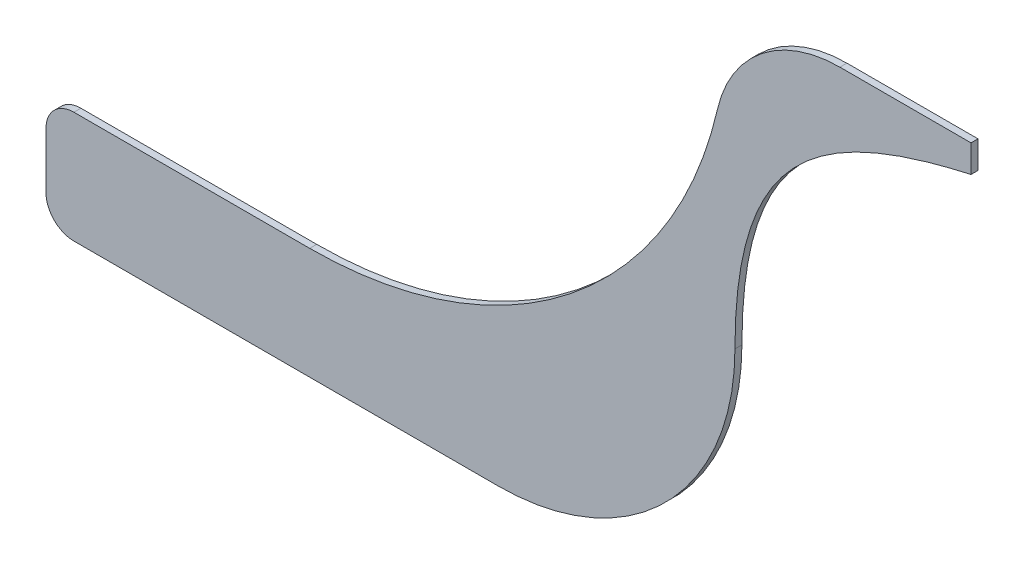
SolidWorks part; units mm, degrees
ref_plane "Front Plane" through (0, 0, 0) normal (0, 0, 1) x (1, 0, 0)
ref_plane "Top Plane" through (0, 0, 0) normal (0, 1, 0) x (1, 0, 0)
ref_plane "Right Plane" through (0, 0, 0) normal (1, 0, 0) x (0, 0, -1)
sketch "Sketch1" plane through (0, 0, 0) normal (0, 0, 1) x (1, 0, 0)
  line L7 (4.7908, -60.96) -> (390.7256, -60.96)
  line L10 (0, 0) -> (37.7775, 0) construction
  line L11 (0, 0) -> (0, 25.207) construction
  line L13 (537.7399, 133.6045) -> (531.2485, 128.3759) construction
  line L14 (532.6011, 126.4746) -> (537.7399, 133.6045) construction
  line L16 (531.2485, 128.3759) -> (532.6011, 126.4746) construction
  line L17 (816.9226, 414.253) -> (643.6796, 374.2567) construction
  line L18 (821.5604, 399.9249) -> (821.5604, 424.8632)
  line L19 (821.5604, 424.8632) -> (702.1701, 424.8632)
  line L20 (219.4859, 40.64) -> (4.7908, 40.64)
  line L21 (-20.6092, 15.24) -> (-20.6092, -35.56)
  line L24 (606.6256, 154.94) -> (606.6256, 89.2688) construction
  line L25 (537.7399, 133.6045) -> (383.6222, 21.6314) construction
  line L33 (821.5604, 399.9249) -> (821.5604, 424.8632)
  line L34 (821.5604, 424.8632) -> (702.1701, 424.8632)
  line L35 (411.4058, 7.8396) -> (183.7775, -13.2146) construction
  line L36 (207.1209, -34.079) -> (-20.7053, -15.2861) construction
  line L37 (603.425, 236.8899) -> (603.8611, 238.0136) construction
  line L38 (603.8611, 238.0136) -> (603.1798, 237.0956) construction
  line L43 (603.1798, 237.0956) -> (603.425, 236.8899) construction
  line L44 (603.3024, 236.9927) -> (521.6684, 139.7051) construction
  arc A7 (-20.6092, 15.24) -> (4.7908, 40.64) centre (4.7908, 15.24) cw
  arc A8 (-20.6092, -35.56) -> (4.7908, -60.96) centre (4.7908, -35.56) ccw
  arc A9 (390.7256, -60.96) -> (606.6256, 154.94) centre (390.7256, 154.94) ccw
  arc A23 (702.1701, 424.8632) -> (590.7814, 336.1963) centre (702.1701, 310.5632) ccw
  arc A24 (219.4859, 40.64) -> (590.7814, 336.1963) centre (219.4859, 421.64) ccw
  arc A34 (702.1701, 424.8632) -> (590.7814, 336.1963) centre (702.1701, 310.5632) ccw
  spline S1 degree 3 poles (205.7746, -34.3419) (207.4601, -34.0418) (205.7508, -34.1146) (204.3345, -34.0688) (200.8985, -34.0935) (196.6585, -34.0726) (191.0976, -34.0348) (184.5159, -33.9471) (176.9076, -33.8001) (168.395, -33.5665) (159.0697, -33.2317) (149.0451, -32.7724) (138.436, -32.1785) (127.3624, -31.4371) (115.9466, -30.55) (104.3139, -29.5199) (92.5883, -28.3721) (80.9024, -27.1095) (69.4319, -25.836) (58.3151, -24.3819) (47.6594, -22.7227) (37.4925, -20.9531) (27.8974, -19.1388) (18.9599, -17.3727) (10.7546, -15.7426) (3.3636, -14.3246) (-3.143, -13.1917) (-8.6962, -12.4233) (-13.2419, -12.045) (-16.7424, -12.1507) (-19.2577, -12.6358) (-20.8762, -14.0515) (-20.6577, -16.1973) (-19.1168, -18.2836) (-16.513, -20.7346) (-12.6851, -23.4582) (-7.6823, -26.4319) (-1.5097, -29.5261) (5.7688, -32.6504) (14.0872, -35.6766) (23.3521, -38.4968) (33.4604, -40.998) (44.2899, -43.0863) (55.7048, -44.6947) (67.5037, -45.7215) (79.5188, -46.2577) (91.6044, -46.5063) (103.6897, -46.4289) (115.6399, -46.0602) (127.3197, -45.4278) (138.5979, -44.5656) (149.3499, -43.5169) (159.4594, -42.3324) (168.8129, -41.0597) (177.3128, -39.7631) (184.8713, -38.4873) (191.384, -37.2993) (196.865, -36.2379) (201.0292, -35.3765) (204.4026, -34.6928) (205.7746, -34.3419) (207.4601, -34.0418) (205.7508, -34.1146) knots -0.012273 -0.005484 -0.001375 0 0.001366 0.005489 0.012269 0.02165 0.033497 0.04769 0.06403 0.082338 0.102396 0.123959 0.146791 0.170641 0.19524 0.220332 0.245646 0.27091 0.295825 0.31977 0.342911 0.365083 0.386049 0.405629 0.423597 0.43978 0.453966 0.466008 0.475784 0.483219 0.48846 0.492078 0.495706 0.500976 0.508553 0.518608 0.53108 0.545907 0.56292 0.581928 0.60273 0.625094 0.648778 0.673537 0.699099 0.724814 0.750772 0.776731 0.802428 0.827555 0.851851 0.875071 0.896936 0.917223 0.935694 0.952169 0.966419 0.978318 0.987727 0.994516 0.998625 1 1.001366 1.005489 1.012269 only from (207.1209, -34.079) to (207.1209, -34.079) construction
  spline S2 degree 3 poles (410.1256, 7.3468) (411.7335, 7.9351) (410.0628, 7.5665) (408.66, 7.3658) (405.2805, 6.7447) (401.1013, 6.029) (395.6183, 5.1007) (389.1213, 4.0442) (381.6031, 2.8677) (373.1792, 1.6196) (363.9375, 0.33) (353.9854, -0.9585) (343.4344, -2.2158) (332.4003, -3.4086) (321.0039, -4.5174) (309.369, -5.5229) (297.6222, -6.4286) (285.8946, -7.2144) (274.3773, -7.9522) (263.1769, -8.4505) (252.3949, -8.6669) (242.0752, -8.6896) (232.3108, -8.5691) (223.2024, -8.3817) (214.8387, -8.2013) (207.3137, -8.0883) (200.7093, -8.1024) (195.107, -8.31) (190.5647, -8.7267) (187.1357, -9.4388) (184.7428, -10.3532) (183.3948, -12.0284) (183.9825, -14.1037) (185.8624, -15.8908) (188.8522, -17.8524) (193.0949, -19.8699) (198.5381, -21.9297) (205.1542, -23.905) (212.8647, -25.7179) (221.5822, -27.2537) (231.1961, -28.4222) (241.5851, -29.1301) (252.6127, -29.3062) (264.1334, -28.908) (275.9314, -27.8704) (287.8571, -26.312) (299.8022, -24.4582) (311.6906, -22.2833) (323.3952, -19.8451) (334.7877, -17.1941) (345.7448, -14.3866) (356.1514, -11.4868) (365.9016, -8.5648) (374.892, -5.6872) (383.0376, -2.9343) (390.2598, -0.3654) (396.4672, 1.9354) (401.6806, 3.9325) (405.632, 5.5039) (408.8354, 6.763) (410.1256, 7.3468) (411.7335, 7.9351) (410.0628, 7.5665) knots -0.012273 -0.005484 -0.001375 0 0.001366 0.005489 0.012269 0.02165 0.033497 0.04769 0.06403 0.082338 0.102396 0.123959 0.146791 0.170641 0.19524 0.220332 0.245646 0.27091 0.295825 0.31977 0.342911 0.365083 0.386049 0.405629 0.423597 0.43978 0.453966 0.466008 0.475784 0.483219 0.48846 0.492078 0.495706 0.500976 0.508553 0.518608 0.53108 0.545907 0.56292 0.581928 0.60273 0.625094 0.648778 0.673537 0.699099 0.724814 0.750772 0.776731 0.802428 0.827555 0.851851 0.875071 0.896936 0.917223 0.935694 0.952169 0.966419 0.978318 0.987727 0.994516 0.998625 1 1.001366 1.005489 1.012269 only from (411.4058, 7.8396) to (411.4058, 7.8396) construction
  spline S3 degree 3 poles (531.2485, 128.3759) (529.7206, 127.1452) (528.1914, 125.9161) (525.1247, 123.4682) (523.588, 122.2484) (518.9672, 118.6029) (515.8721, 116.1904) (506.5465, 109.0148) (500.2726, 104.3143) (487.609, 95.0831) (481.2187, 90.5532) (468.3373, 81.6412) (461.846, 77.2593) (452.0631, 70.7538) (448.7931, 68.5987) (443.8873, 65.3669) (442.2514, 64.2907) (438.9645, 62.1602) (437.313, 61.1067) (432.3377, 57.977) (428.993, 55.9311) (422.2638, 51.8981) (418.879, 49.9111) (412.0945, 45.959) (408.6946, 43.9953) (403.6168, 41.0142) (401.928, 40.0143) (398.5687, 37.9847) (396.8979, 36.9557) (393.5939, 34.8367) (391.9596, 33.7486) (389.571, 32.0144) (388.7836, 31.4182) (387.2581, 30.1765) (386.5172, 29.5325) (385.4728, 28.4961) (385.1355, 28.1393) (384.4948, 27.3898) (384.1901, 26.9933) (383.6477, 26.1633) (383.4103, 25.7298) (383.1457, 25.0291) (383.0736, 24.7888) (382.9704, 24.304) (382.9387, 24.0579) (382.9256, 23.5565) (382.9452, 23.3073) (383.0394, 22.8216) (383.1144, 22.5809) (383.3112, 22.1218) (383.4316, 21.9051) (383.7147, 21.4961) (383.879, 21.3034) (384.2326, 20.9546) (384.4233, 20.7961) (384.8271, 20.5052) (385.0408, 20.3724) (385.6951, 20.0154) (386.1542, 19.8292) (387.1007, 19.5203) (387.5843, 19.3991) (388.5564, 19.2065) (389.0466, 19.1339) (390.0331, 19.0223) (390.5299, 18.984) (391.5187, 18.9348) (392.0121, 18.9233) (393.4899, 18.9207) (394.4717, 18.9615) (396.431, 19.1021) (397.4082, 19.2028) (399.3591, 19.4513) (400.3327, 19.5995) (402.2768, 19.9365) (403.2473, 20.1253) (406.138, 20.7418) (408.0434, 21.2198) (413.7065, 22.818) (417.4116, 24.1008) (422.8837, 26.2897) (424.6959, 27.0653) (428.2804, 28.6954) (430.0482, 29.5478) (435.2838, 32.2084) (438.6839, 34.1201) (445.322, 38.191) (448.5602, 40.3499) (454.8861, 44.8975) (457.9674, 47.2959) (462.5391, 50.9704) (464.053, 52.2105) (467.06, 54.7224) (468.5523, 55.9931) (475.9447, 62.401) (481.6548, 67.7138) (492.7274, 78.6576) (498.0893, 84.2891) (508.4939, 95.8441) (513.5362, 101.7682) (520.8641, 110.8696) (523.2672, 113.9397) (526.8124, 118.5991) (527.9841, 120.1614) (530.3075, 123.3044) (531.457, 124.8871) (532.6011, 126.4746) knots 0 0 0 0 0.015625 0.015625 0.03125 0.03125 0.0625 0.0625 0.125 0.125 0.1875 0.1875 0.25 0.25 0.28125 0.28125 0.296875 0.296875 0.3125 0.3125 0.34375 0.34375 0.375 0.375 0.40625 0.40625 0.421875 0.421875 0.4375 0.4375 0.453125 0.453125 0.460938 0.460938 0.46875 0.46875 0.472656 0.472656 0.476563 0.476563 0.480469 0.480469 0.482422 0.482422 0.484375 0.484375 0.486328 0.486328 0.488281 0.488281 0.490234 0.490234 0.492188 0.492188 0.494141 0.494141 0.496094 0.496094 0.5 0.5 0.503906 0.503906 0.507813 0.507813 0.511719 0.511719 0.515625 0.515625 0.523438 0.523438 0.53125 0.53125 0.539063 0.539063 0.546875 0.546875 0.5625 0.5625 0.59375 0.59375 0.609375 0.609375 0.625 0.625 0.65625 0.65625 0.6875 0.6875 0.71875 0.71875 0.734375 0.734375 0.75 0.75 0.8125 0.8125 0.875 0.875 0.9375 0.9375 0.96875 0.96875 0.984375 0.984375 1 1 1 1 construction
  spline S5 degree 3 poles (606.6256, 154.94) (606.6256, 316.01) (681.9854, 368.5237) (821.5604, 399.9249) knots 0 0 0 0 1 1 1 1
  spline S6 degree 3 poles (205.7746, -34.3419) (207.4601, -34.0418) (205.7508, -34.1146) (204.3345, -34.0688) (200.8985, -34.0935) (196.6585, -34.0726) (191.0976, -34.0348) (184.5159, -33.9471) (176.9076, -33.8001) (168.395, -33.5665) (159.0697, -33.2317) (149.0451, -32.7724) (138.436, -32.1785) (127.3624, -31.4371) (115.9466, -30.55) (104.3139, -29.5199) (92.5883, -28.3721) (80.9024, -27.1095) (69.4319, -25.836) (58.3151, -24.3819) (47.6594, -22.7227) (37.4925, -20.9531) (27.8974, -19.1388) (18.9599, -17.3727) (10.7546, -15.7426) (3.3636, -14.3246) (-3.143, -13.1917) (-8.6962, -12.4233) (-13.2419, -12.045) (-16.7424, -12.1507) (-19.2577, -12.6358) (-20.8762, -14.0515) (-20.6577, -16.1973) (-19.1168, -18.2836) (-16.513, -20.7346) (-12.6851, -23.4582) (-7.6823, -26.4319) (-1.5097, -29.5261) (5.7688, -32.6504) (14.0872, -35.6766) (23.3521, -38.4968) (33.4604, -40.998) (44.2899, -43.0863) (55.7048, -44.6947) (67.5037, -45.7215) (79.5188, -46.2577) (91.6044, -46.5063) (103.6897, -46.4289) (115.6399, -46.0602) (127.3197, -45.4278) (138.5979, -44.5656) (149.3499, -43.5169) (159.4594, -42.3324) (168.8129, -41.0597) (177.3128, -39.7631) (184.8713, -38.4873) (191.384, -37.2993) (196.865, -36.2379) (201.0292, -35.3765) (204.4026, -34.6928) (205.7746, -34.3419) (207.4601, -34.0418) (205.7508, -34.1146) knots -0.012273 -0.005484 -0.001375 0 0.001366 0.005489 0.012269 0.02165 0.033497 0.04769 0.06403 0.082338 0.102396 0.123959 0.146791 0.170641 0.19524 0.220332 0.245646 0.27091 0.295825 0.31977 0.342911 0.365083 0.386049 0.405629 0.423597 0.43978 0.453966 0.466008 0.475784 0.483219 0.48846 0.492078 0.495706 0.500976 0.508553 0.518608 0.53108 0.545907 0.56292 0.581928 0.60273 0.625094 0.648778 0.673537 0.699099 0.724814 0.750772 0.776731 0.802428 0.827555 0.851851 0.875071 0.896936 0.917223 0.935694 0.952169 0.966419 0.978318 0.987727 0.994516 0.998625 1 1.001366 1.005489 1.012269 only from (207.1209, -34.079) to (207.1209, -34.079) construction
  spline S7 degree 3 poles (603.1798, 237.0956) (603.1409, 237.0431) (602.9853, 236.8334) (602.6357, 236.3634) (602.0551, 235.5834) (601.2454, 234.4997) (600.2104, 233.1201) (598.9544, 231.4547) (597.4824, 229.5162) (595.8009, 227.3185) (593.9169, 224.8782) (591.8387, 222.2129) (589.575, 219.3427) (587.1364, 216.2879) (584.5343, 213.0706) (581.7817, 209.713) (578.8924, 206.2385) (575.8828, 202.6698) (572.77, 199.0301) (569.5733, 195.3419) (566.3136, 191.6266) (563.0126, 187.9061) (559.6953, 184.1993) (556.3835, 180.528) (553.1121, 176.9007) (549.84, 173.3942) (546.6014, 170.018) (543.4269, 166.7835) (540.349, 163.6997) (537.3998, 160.7746) (534.6111, 158.0147) (532.0131, 155.426) (529.6348, 153.0132) (527.5024, 150.7813) (525.6402, 148.7341) (524.069, 146.8754) (522.8063, 145.2082) (521.8652, 143.7336) (521.2551, 142.448) (520.9798, 141.3371) (521.0894, 140.3657) (521.655, 139.6233) (522.5649, 139.18) (523.7583, 139.0042) (525.2335, 139.0722) (526.9899, 139.385) (529.0158, 139.9473) (531.2916, 140.7664) (533.793, 141.8474) (536.4921, 143.1961) (539.3588, 144.8158) (542.3616, 146.7091) (545.4677, 148.8765) (548.6451, 151.3156) (551.8616, 154.0221) (555.0866, 156.9882) (558.291, 160.2034) (561.4475, 163.6541) (564.5321, 167.3227) (567.5175, 171.1898) (570.4578, 175.1744) (573.3277, 179.2579) (576.1155, 183.4101) (578.8075, 187.6023) (581.3928, 191.8041) (583.8604, 195.9854) (586.2013, 200.1152) (588.4078, 204.1624) (590.473, 208.0964) (592.3918, 211.8867) (594.1595, 215.5037) (595.7733, 218.9185) (597.2316, 222.1031) (598.5327, 225.0316) (599.677, 227.679) (600.6649, 230.0229) (601.4974, 232.0427) (602.1759, 233.7207) (602.7018, 235.0418) (603.0761, 235.9942) (603.3005, 236.5691) (603.4001, 236.8256) (603.425, 236.8899) knots 0 0 0 0 0.000751 0.002998 0.006728 0.011917 0.018533 0.026535 0.035872 0.046487 0.058313 0.071277 0.085299 0.100293 0.116166 0.13282 0.150153 0.16806 0.186431 0.205154 0.224112 0.243191 0.262273 0.281239 0.299973 0.318368 0.336314 0.3537 0.370414 0.38635 0.401402 0.415472 0.428469 0.440308 0.45092 0.460246 0.46825 0.474922 0.480304 0.484529 0.48793 0.491137 0.494783 0.499272 0.504867 0.511675 0.51972 0.528986 0.53943 0.550997 0.56362 0.577229 0.591748 0.607102 0.623214 0.640008 0.657405 0.675329 0.693699 0.712432 0.731423 0.750565 0.769746 0.788854 0.807777 0.826399 0.844608 0.86229 0.879335 0.895632 0.911077 0.925567 0.939006 0.951301 0.962367 0.972127 0.980511 0.987456 0.992913 0.99684 0.999209 1 1 1 1 construction
  spline S10 degree 3 poles (816.9226, 414.253) (814.991, 414.5617) (813.049, 414.818) (808.9639, 415.3173) (806.8198, 415.5508) (802.5312, 415.9834) (800.3856, 416.1814) (793.9457, 416.7346) (789.6486, 417.0496) (781.0476, 417.5883) (776.7437, 417.8104) (768.1285, 418.1547) (763.8218, 418.2766) (755.2201, 418.3906) (750.9239, 418.3821) (742.3433, 418.198) (738.0588, 418.0232) (729.5085, 417.409) (725.2435, 416.9592) (716.7379, 415.7128) (712.4972, 414.919) (707.2126, 413.695) (706.1553, 413.4382) (704.0497, 412.903) (703.0014, 412.6245) (699.8702, 411.7562) (697.8008, 411.1336) (691.648, 409.1326) (687.6203, 407.6199) (679.7164, 404.2296) (675.8381, 402.3571) (670.1509, 399.2341) (668.2772, 398.1401) (664.5811, 395.8285) (662.7734, 394.6205) (659.2586, 392.0881) (657.5502, 390.7633) (654.2541, 387.9693) (652.6655, 386.5013) (650.404, 384.1539) (649.6704, 383.3473) (648.2535, 381.6739) (647.5744, 380.812) (646.2982, 379.0423) (645.7, 378.1322) (644.6035, 376.249) (644.1056, 375.2755) (643.6796, 374.2567) knots 0.548291 0.548291 0.548291 0.548291 0.5625 0.5625 0.578125 0.578125 0.59375 0.59375 0.625 0.625 0.65625 0.65625 0.6875 0.6875 0.71875 0.71875 0.75 0.75 0.78125 0.78125 0.8125 0.8125 0.820313 0.820313 0.828125 0.828125 0.84375 0.84375 0.875 0.875 0.90625 0.90625 0.921875 0.921875 0.9375 0.9375 0.953125 0.953125 0.96875 0.96875 0.976563 0.976563 0.984375 0.984375 0.992188 0.992188 1 1 1 1 construction
  spline S11 degree 3 poles (643.6796, 374.2567) (643.653, 374.1878) (643.6253, 374.115) (643.5722, 373.973) (643.4935, 373.7598) (643.4183, 373.5456) (643.2727, 373.1158) (643.182, 372.8276) (642.9315, 371.9569) (642.7929, 371.3686) (642.5851, 370.173) (642.5174, 369.5695) (642.4755, 368.3658) (642.4977, 367.7633) (642.6745, 366.5565) (642.831, 365.9709) (643.1405, 365.2763) (643.2084, 365.1385) (643.3581, 364.8732) (643.44, 364.7455) (643.6158, 364.4987) (643.7092, 364.3792) (643.9182, 364.156) (644.0316, 364.051) (644.2733, 363.8686) (644.403, 363.7908) (644.674, 363.6527) (644.815, 363.5907) (645.2425, 363.4332) (645.5366, 363.363) (646.1329, 363.2537) (646.4363, 363.2189) (647.0412, 363.1754) (647.3441, 363.1663) (647.9508, 363.1701) (648.2558, 363.1832) (648.8565, 363.2272) (649.1531, 363.258) (650.0343, 363.3708) (650.6107, 363.4726) (652.3227, 363.8183) (653.4392, 364.1075) (656.7414, 365.088) (658.8823, 365.8857) (663.1129, 367.6024) (665.2004, 368.5269) (669.3454, 370.4468) (671.4027, 371.4429) (675.5077, 373.4581) (677.5553, 374.477) (681.6557, 376.5031) (683.7092, 377.5082) (689.8891, 380.4775) (694.0342, 382.3973) (700.3018, 385.1582) (702.3992, 386.0593) (706.6117, 387.8188) (708.7278, 388.6774) (715.0969, 391.1769) (719.374, 392.7389) (727.9864, 395.6662) (732.3221, 397.0302) (741.0367, 399.6128) (745.4151, 400.8331) (754.2089, 403.1487) (758.6242, 404.2444) (767.4925, 406.3084) (771.949, 407.2775) (780.8821, 409.0634) (785.3596, 409.8808) (794.3365, 411.3658) (798.8355, 412.0354) (807.8527, 413.2437) (812.3709, 413.7814) (816.907, 414.2513) (816.9148, 414.2521) (816.9226, 414.253) knots 0 0 0 0 0.000488 0.000488 0.000977 0.001953 0.001953 0.003906 0.003906 0.007812 0.007812 0.011719 0.011719 0.015625 0.015625 0.019531 0.019531 0.020508 0.020508 0.021484 0.021484 0.022461 0.022461 0.023438 0.023438 0.024414 0.024414 0.025391 0.025391 0.027344 0.027344 0.029297 0.029297 0.03125 0.03125 0.033203 0.033203 0.035156 0.035156 0.039063 0.039063 0.046875 0.046875 0.0625 0.0625 0.078125 0.078125 0.09375 0.09375 0.109375 0.109375 0.125 0.125 0.15625 0.15625 0.171875 0.171875 0.1875 0.1875 0.21875 0.21875 0.25 0.25 0.28125 0.28125 0.3125 0.3125 0.34375 0.34375 0.375 0.375 0.40625 0.40625 0.4375 0.4375 0.437554 0.437554 0.437554 0.437554 construction
  point P18 (207.1209, -34.079)
  dimension "D3" = 20.6092
  dimension "D5" = 25.4
  dimension "D6" = 25.4
  dimension "D7" = 381
  dimension "D8" = 114.3
  dimension "D11" = 214.6951
  dimension "D12" = 101.6
  dimension "D14" = 215.9
  dimension "D9" = 119.3904
  dimension "D4" = 60.96
  dimension "D17" = 842.1696
  dimension "D22" = 90
  dimension "D23" = 90
extrude "Boss-Extrude1" add sketch "Sketch1" along normal blind 6.35
